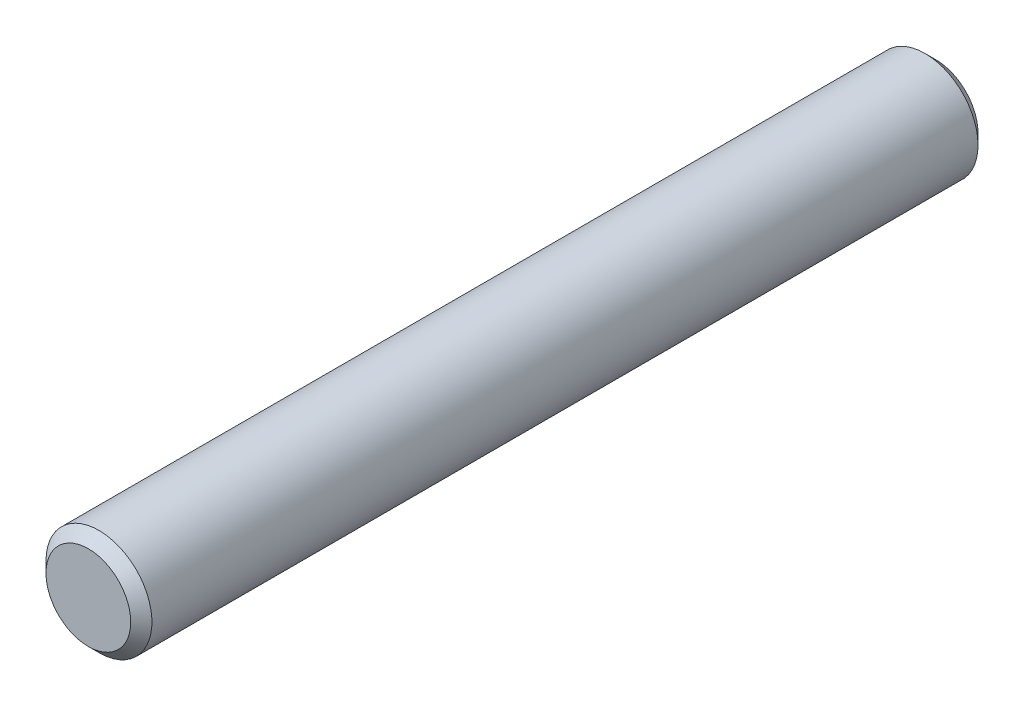
SolidWorks part; units mm, degrees
material "3003 Alloy"
ref_plane "Front" through (0, 0, 0) normal (0, 0, 1) x (1, 0, 0)
ref_plane "Top" through (0, 0, 0) normal (0, 1, 0) x (1, 0, 0)
ref_plane "Right" through (0, 0, 0) normal (1, 0, 0) x (0, 0, -1)
sketch "Sketch1" plane through (0, 0, 0) normal (0, 0, 1) x (1, 0, 0)
  circle A0 centre (0, 0) radius 4.7625
  dimension "dia" = 9.525
sketch "Sketch3" plane through (0, 0, 0) normal (0, 0, 1) x (1, 0, 0)
  circle A0 centre (0, 0) radius 4.7625 construction
  circle A1 centre (0, 0) radius 4.7625
extrude "Boss-Extrude1" add sketch "Sketch3" along normal mid plane 76.2
sketch "Sketch2" plane through (0, 0, 0) normal (1, 0, 0) x (0, 0, -1)
  line L0 (38.1, 4.7625) -> (-38.1, 4.7625) construction
  point P0 (-38.1, 4.7625)
  point P1 (38.1, 4.7625)
  point P2 (19.05, 4.7625)
  point P8 (-19.05, 4.7625)
  dimension "D1" = 19.05
  dimension "D2" = 19.05
chamfer "Chamfer1" distance 0.9525 angle 45 2 edges at (4.7625, 0, -38.1) (4.7625, 0, 38.1)
equation "\"D1@Chamfer1\" = \"dia@Sketch1\" * .1"
equation "\"D1@Sketch2\" = \"dia@Sketch1\" * 2"
equation "\"D2@Sketch2\"=\"D1@Sketch2\""
